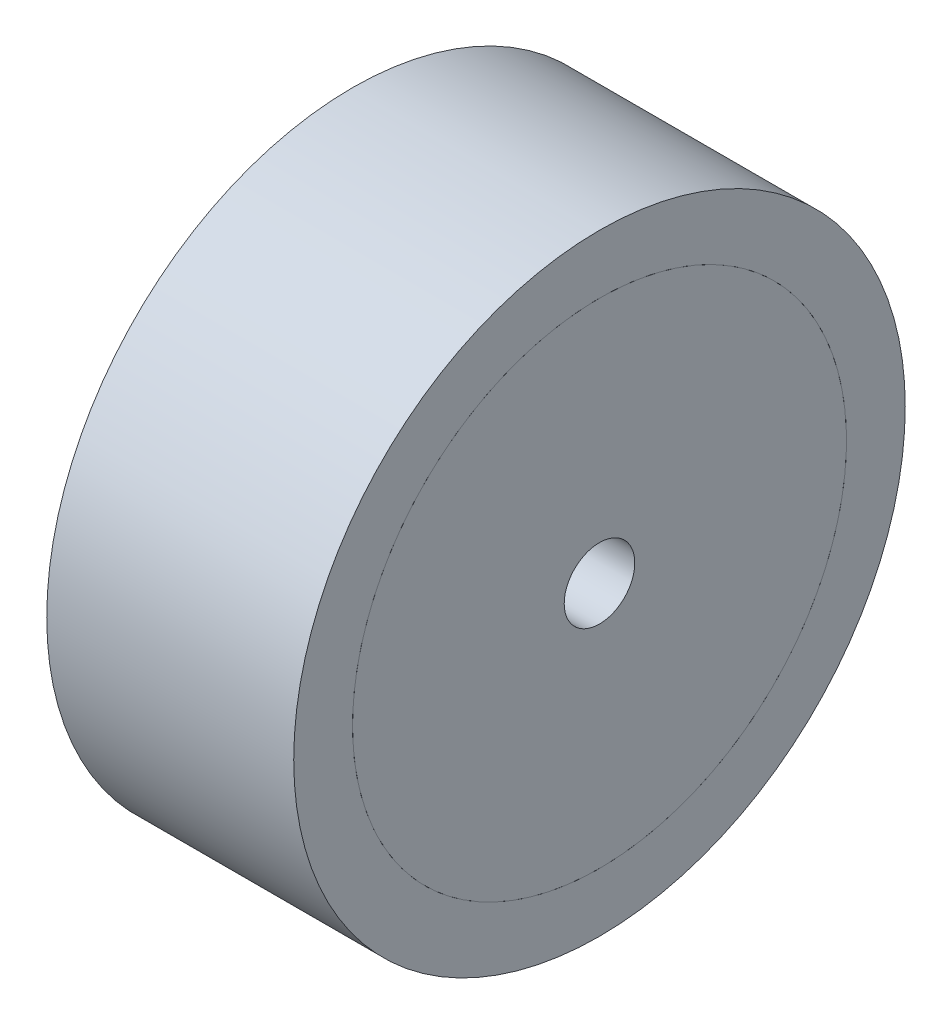
SolidWorks part; units mm, degrees
ref_plane "Front Plane" through (0, 0, 0) normal (0, 0, 1) x (1, 0, 0)
ref_plane "Top Plane" through (0, 0, 0) normal (0, 1, 0) x (1, 0, 0)
ref_plane "Right Plane" through (0, 0, 0) normal (1, 0, 0) x (0, 0, -1)
sketch "Sketch1" plane through (0, 0, 0) normal (1, 0, 0) x (0, 0, -1)
  circle A0 centre (0, 0) radius 21
  circle A1 centre (0, 0) radius 3
  dimension "D1" = 42
  dimension "D2" = 6
extrude "Boss-Extrude1" add sketch "Sketch1" along normal blind 21
sketch "Sketch2" plane through (21, 0, 0) normal (1, 0, 0) x (0, 0, -1)
  circle A0 centre (0, 0) radius 26
  circle A1 centre (0, 0) radius 21 construction
  circle A2 centre (0, 0) radius 21
  dimension "D1" = 52
extrude "Boss-Extrude2" add sketch "Sketch2" against normal up to surface (21 mm away) separate body contours A2 | A0 up to face at (0, 0, -21)
